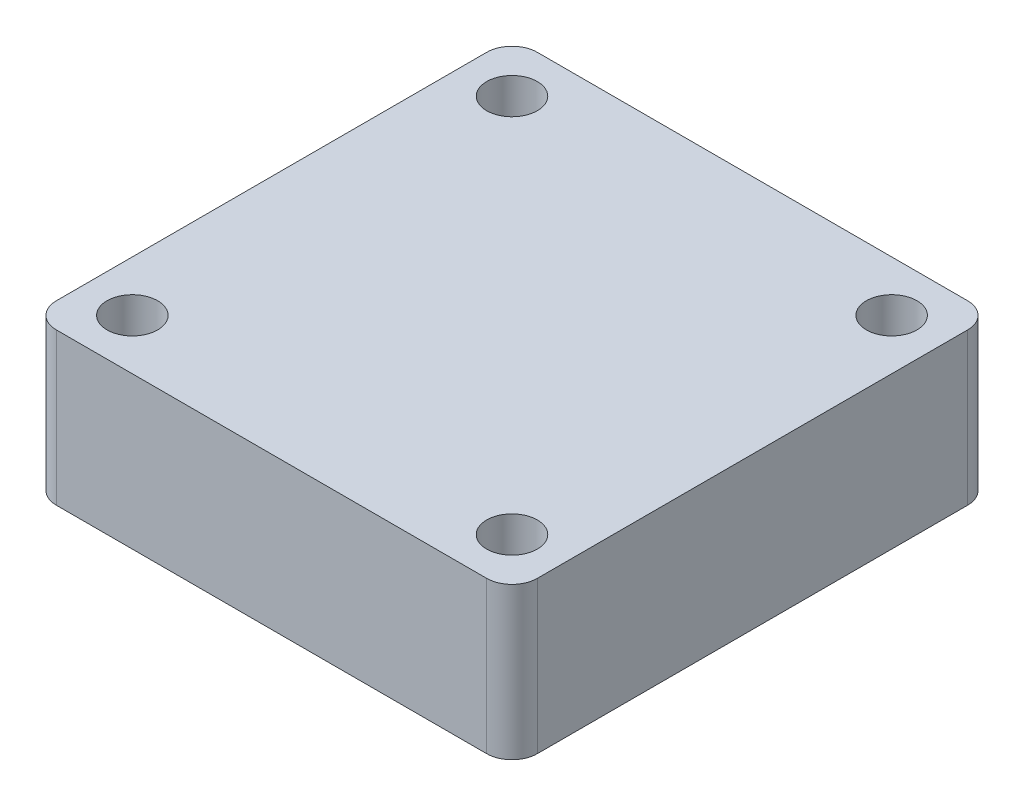
SolidWorks part; units mm, degrees
ref_plane "Спереди" through (0, 0, 0) normal (0, 0, 1) x (1, 0, 0)
ref_plane "Сверху" through (0, 0, 0) normal (0, 1, 0) x (1, 0, 0)
ref_plane "Справа" through (0, 0, 0) normal (1, 0, 0) x (0, 0, -1)
sketch "Эскиз1" plane through (0, 0, 0) normal (0, 1, 0) x (1, 0, 0)
  line L0 (0, 0) -> (19, 0)
  line L1 (19, 0) -> (19, 19)
  line L2 (0, 0) -> (0, 19)
  line L3 (0, 19) -> (19, 19)
  line L5 (2, 2) -> (17, 2) construction
  line L6 (2, 2) -> (2, 17) construction
  line L7 (2, 17) -> (17, 17) construction
  line L8 (17, 2) -> (17, 17) construction
  circle A0 centre (2, 17) radius 1
  circle A1 centre (17, 17) radius 1
  circle A2 centre (17, 2) radius 1
  circle A3 centre (2, 2) radius 1
  dimension "D1" = 19
  dimension "D2" = 2
  dimension "D3" = 15
  dimension "D4" = 15
  dimension "D5" = 2
  dimension "D6" = 19
extrude "Бобышка-Вытянуть1" add sketch "Эскиз1" along normal blind 6
fillet "Скругление1" radius 1 4 edges at (19, 3, 0) (0, 3, 0) (0, 3, -19) (19, 3, -19)
